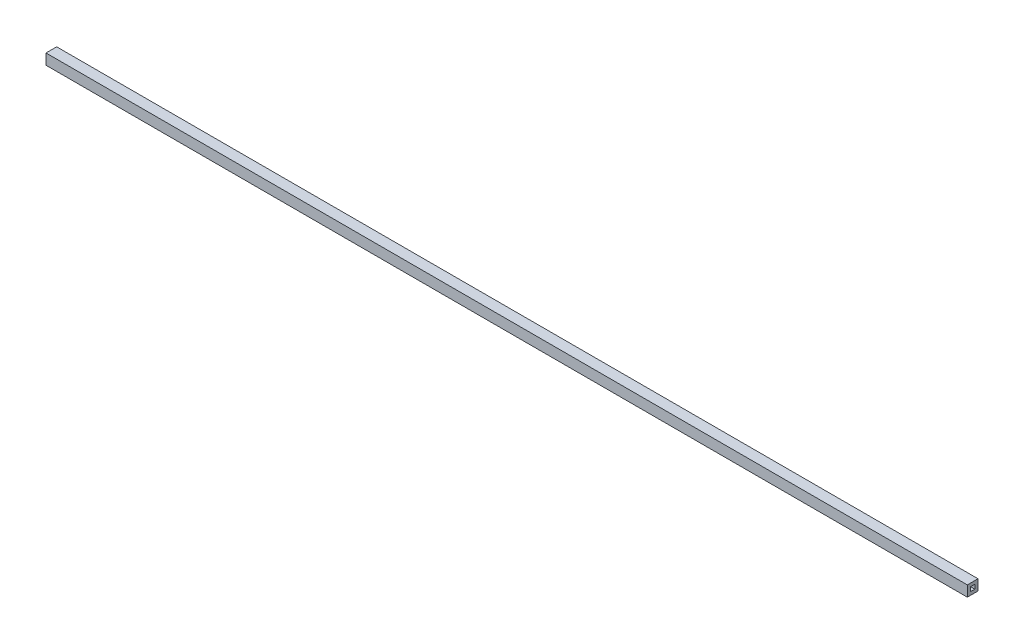
SolidWorks part; units mm, degrees
material "7075-T6 (SN)"
ref_plane "Front Plane" through (0, 0, 0) normal (0, 0, 1) x (1, 0, 0)
ref_plane "Top Plane" through (0, 0, 0) normal (0, 1, 0) x (1, 0, 0)
ref_plane "Right Plane" through (0, 0, 0) normal (1, 0, 0) x (0, 0, -1)
sketch "Sketch1" plane through (0, 0, 0) normal (1, 0, 0) x (0, 0, -1)
  line L1 (-2.5, 2.5) -> (2.5, 2.5)
  line L2 (-2.5, 2.5) -> (-2.5, -2.5)
  line L3 (-2.5, -2.5) -> (2.5, -2.5)
  line L4 (2.5, 2.5) -> (2.5, -2.5)
  line L5 (-2.5, 2.5) -> (2.5, -2.5) construction
  line L6 (-2.5, -2.5) -> (2.5, 2.5) construction
  line L7 (-1, 1) -> (1, 1)
  line L8 (-1, 1) -> (-1, -1)
  line L9 (-1, -1) -> (1, -1)
  line L10 (1, 1) -> (1, -1)
  line L11 (-1, 1) -> (1, -1) construction
  line L12 (-1, -1) -> (1, 1) construction
  point P0 (0, 0)
  point P6 (0, 0)
  dimension "D1" = 5
  dimension "D2" = 1.5
extrude "Boss-Extrude1" add sketch "Sketch1" along normal blind 432
